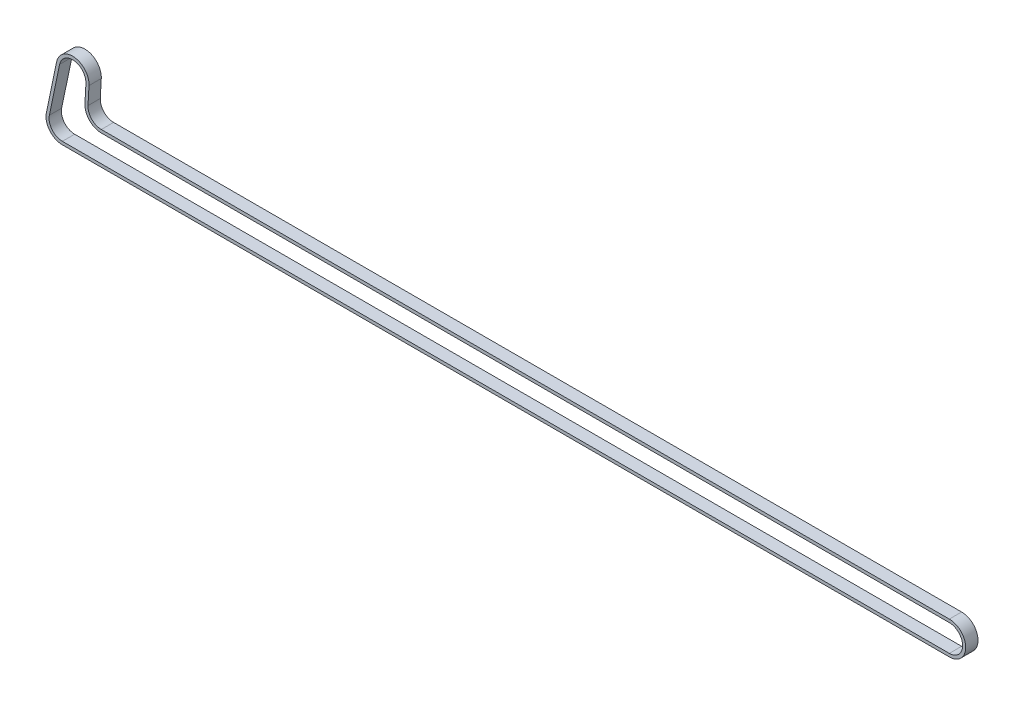
SolidWorks part; units mm, degrees
material "Rubber"
ref_plane "Front Plane" through (0, 0, 0) normal (0, 0, 1) x (1, 0, 0)
ref_plane "Top Plane" through (0, 0, 0) normal (0, 1, 0) x (1, 0, 0)
ref_plane "Right Plane" through (0, 0, 0) normal (1, 0, 0) x (0, 0, -1)
sketch "Sketch1" plane through (0, 0, 0) normal (0, 0, 1) x (1, 0, 0)
  line L0 (216.5, 14) -> (-197.5, 14)
  line L1 (-204.9887, 21.9114) -> (-204.5105, 30.616)
  line L2 (-218.3529, 32.4277) -> (-223.3529, 8.4277)
  line L3 (-216.5, 0) -> (216.5, 0)
  arc A0 (-197.5, 14) -> (-204.9887, 21.9114) centre (-197.5, 21.5) cw
  arc A1 (-223.3529, 8.4277) -> (-216.5, 0) centre (-216.5, 7) ccw
  arc A2 (216.5, 0) -> (216.5, 14) centre (216.5, 7) ccw
  arc A3 (-204.5105, 30.616) -> (-218.3529, 32.4277) centre (-211.5, 31) ccw
  dimension "D1" = 7
  dimension "D2" = 433
  dimension "D6" = 7.5
  dimension "D3" = 24
  dimension "D4" = 14
  dimension "D5" = 5
extrude "Extrude-Thin1" add sketch "Sketch1" along normal mid plane 6 thin
